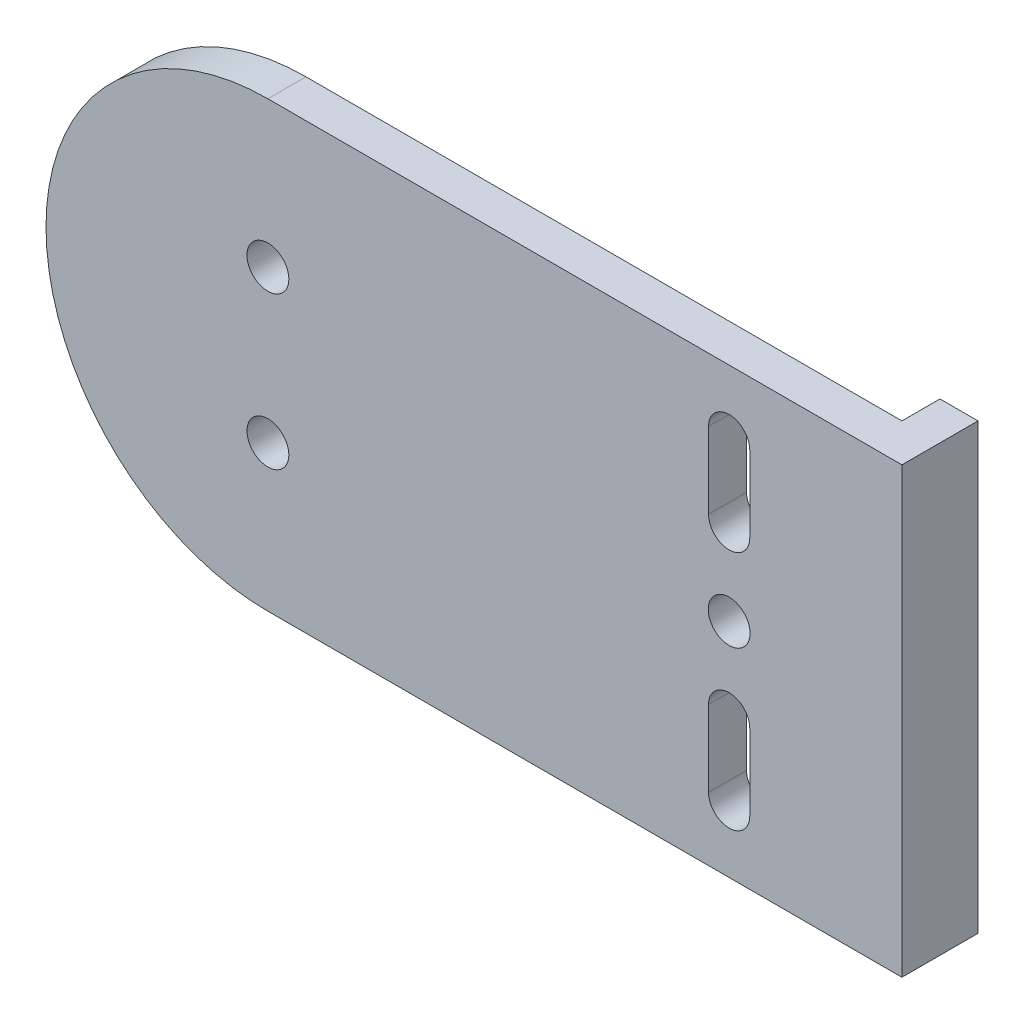
SolidWorks part; units mm, degrees
material "POM 乙缩醛共聚物"
ref_plane "前视基准面" through (0, 0, 0) normal (0, 0, 1) x (1, 0, 0)
ref_plane "上视基准面" through (0, 0, 0) normal (0, 1, 0) x (1, 0, 0)
ref_plane "右视基准面" through (0, 0, 0) normal (1, 0, 0) x (0, 0, -1)
sketch "草图1" plane through (0, 0, 0) normal (0, 0, 1) x (1, 0, 0)
  line L0 (0, 17.5) -> (50, 17.5)
  line L1 (50, 17.5) -> (50, -17.5)
  line L2 (50, -17.5) -> (0, -17.5)
  line L3 (34.75, 12.5) -> (34.75, 6.5)
  line L4 (38, 6.5) -> (38, 12.5)
  line L5 (34.75, -6.5) -> (34.75, -12.5)
  line L6 (38, -12.5) -> (38, -6.5)
  line L7 (0, 0) -> (0, 17.5) construction
  line L8 (0, 0) -> (0, -17.5) construction
  arc A0 (0, 17.5) -> (0, -17.5) centre (0, 0) ccw
  arc A2 (34.75, 6.5) -> (38, 6.5) centre (36.375, 6.5) ccw
  arc A3 (38, 12.5) -> (34.75, 12.5) centre (36.375, 12.5) ccw
  arc A4 (34.75, -12.5) -> (38, -12.5) centre (36.375, -12.5) ccw
  arc A5 (38, -6.5) -> (34.75, -6.5) centre (36.375, -6.5) ccw
  circle A6 centre (36.375, 0) radius 1.65
  circle A13 centre (0, 6) radius 1.65
  circle A14 centre (0, -6) radius 1.65
  point P26 (0, 8.75)
  dimension "D1" = 17.5
  dimension "D3" = 3.3
  dimension "D4" = 3.25
  dimension "D11" = 3.3
  dimension "D12" = 3.3
  dimension "D13" = 12
  dimension "D2" = 50
  dimension "D5" = 6
  dimension "D6" = 6
  dimension "D7" = 12
  dimension "D8" = 5
  dimension "D9" = 12
  dimension "D10" = 5
  dimension "D14" = 6
extrude "凸台-拉伸1" add sketch "草图1" along normal blind 3
sketch "草图2" plane through (0, 0, 3) normal (0, 0, 1) x (1, 0, 0)
  line L0 (0, -17.5) -> (50, -17.5) construction
  line L1 (50, 17.5) -> (47, 17.5)
  line L2 (50, 17.5) -> (50, -17.5)
  line L3 (50, -17.5) -> (47, -17.5)
  line L4 (47, 17.5) -> (47, -17.5)
  dimension "D1" = 3
extrude "凸台-拉伸2" add sketch "草图2" against normal blind 6
